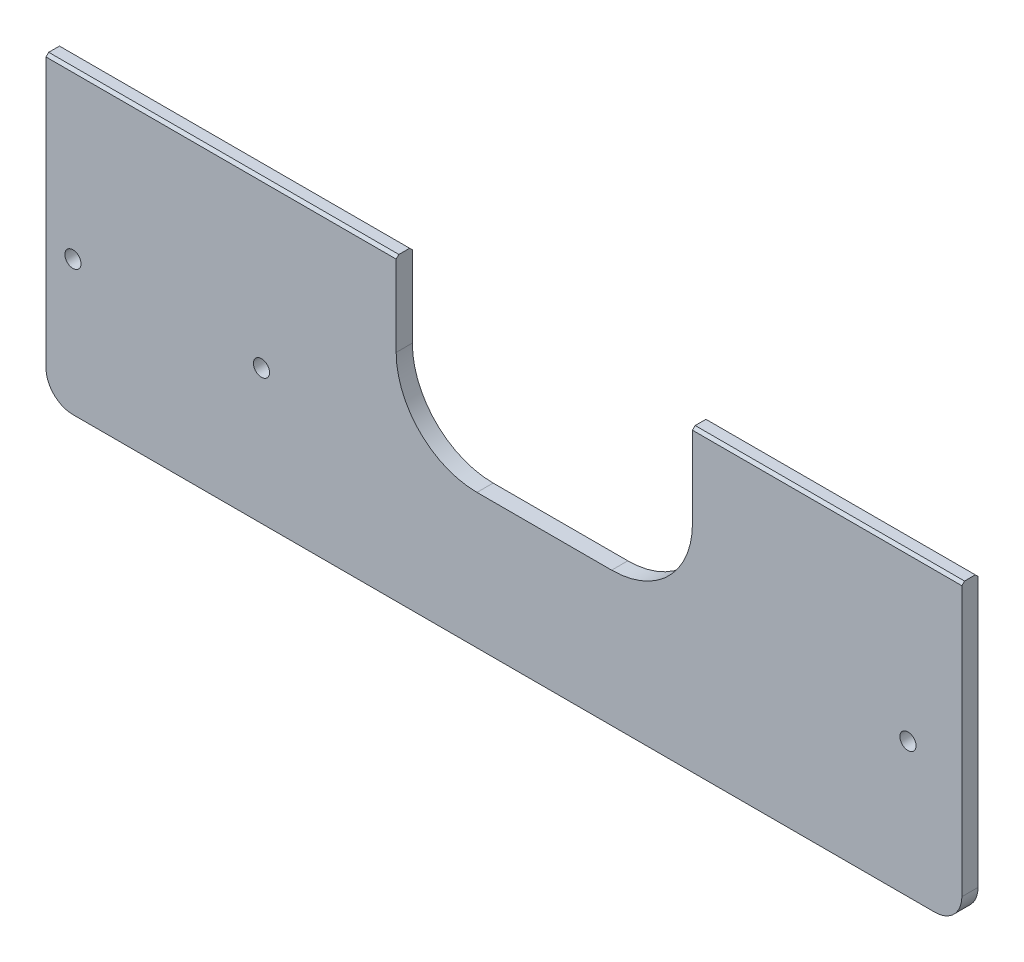
SolidWorks part; units mm, degrees
ref_plane "前视基准面" through (0, 0, 0) normal (0, 0, 1) x (1, 0, 0)
ref_plane "上视基准面" through (0, 0, 0) normal (0, 1, 0) x (1, 0, 0)
ref_plane "右视基准面" through (0, 0, 0) normal (1, 0, 0) x (0, 0, -1)
other "Configuration Table"
sketch "草图1" plane through (0, 0, 0) normal (0, 0, 1) x (1, 0, 0)
  line L1 (-100, 15) -> (70, 15)
  line L2 (-100, 15) -> (-100, -40.5)
  line L3 (-100, -40.5) -> (70, -40.5)
  line L4 (70, 15) -> (70, -40.5)
  dimension "D1" = 170
  dimension "D2" = 55.5
  dimension "D3" = 15
  dimension "D4" = 100
extrude "凸台-拉伸1" add sketch "草图1" along normal blind 3
sketch "草图2" plane through (0, 0, 3) normal (0, 0, 1) x (1, 0, 0)
  circle A0 centre (60, -15.5) radius 1.5
  circle A1 centre (-60, -15.5) radius 1.5
  point P4 (-60, 0)
  point P6 (-58.5944, -12.9109)
  point P7 (0, 0)
  point P8 (0, 0)
  point P9 (61.276, -12.3082)
  dimension "D1" = 3
  dimension "D2" = 3
  dimension "D3" = 120
  dimension "D4" = 60
  dimension "D5" = 15.5
extrude "切除-拉伸1" cut sketch "草图2" against normal blind 3
sketch "草图3" plane through (0, 0, 3) normal (0, 0, 1) x (1, 0, 0)
  line L0 (-20, -0.5) -> (5, -0.5) construction
  line L2 (-20, -15.5) -> (5, -15.5)
  line L3 (-35, -0.5) -> (-35, 15)
  line L4 (70, 15) -> (-100, 15) construction
  line L5 (-35, 15) -> (20, 15)
  line L6 (20, 15) -> (20, -0.5)
  arc A0 (-35, -0.5) -> (-20, -15.5) centre (-20, -0.5) ccw
  arc A1 (5, -15.5) -> (20, -0.5) centre (5, -0.5) ccw
  point P2 (-7.5, -0.5)
  dimension "D1" = 15
  dimension "D2" = 0.5
  dimension "D3" = 25
  dimension "D4" = 20
extrude "切除-拉伸2" cut sketch "草图3" against normal blind 3
fillet "圆角1" radius 5 2 edges at (-100, -40.5, 1.5) (70, -40.5, 1.5)
sketch "草图4" plane through (0, 0, 3) normal (0, 0, 1) x (1, 0, 0)
  circle A0 centre (-95, -15.5) radius 1.5
  circle A1 centre (-60, -15.5) radius 1.5 construction
  point P4 (-91.3807, 0)
  point P6 (0, 0)
  point P7 (-94.9662, -13.9624)
  dimension "D1" = 35
  dimension "D2" = 3
  dimension "D3" = 15.5
extrude "切除-拉伸3" cut sketch "草图4" against normal blind 3
chamfer "倒角1" distance 0.5 angle 45 4 edges at (45, 15, 0) (-67.5, 15, 0) (45, 15, 3) (-67.5, 15, 3)
